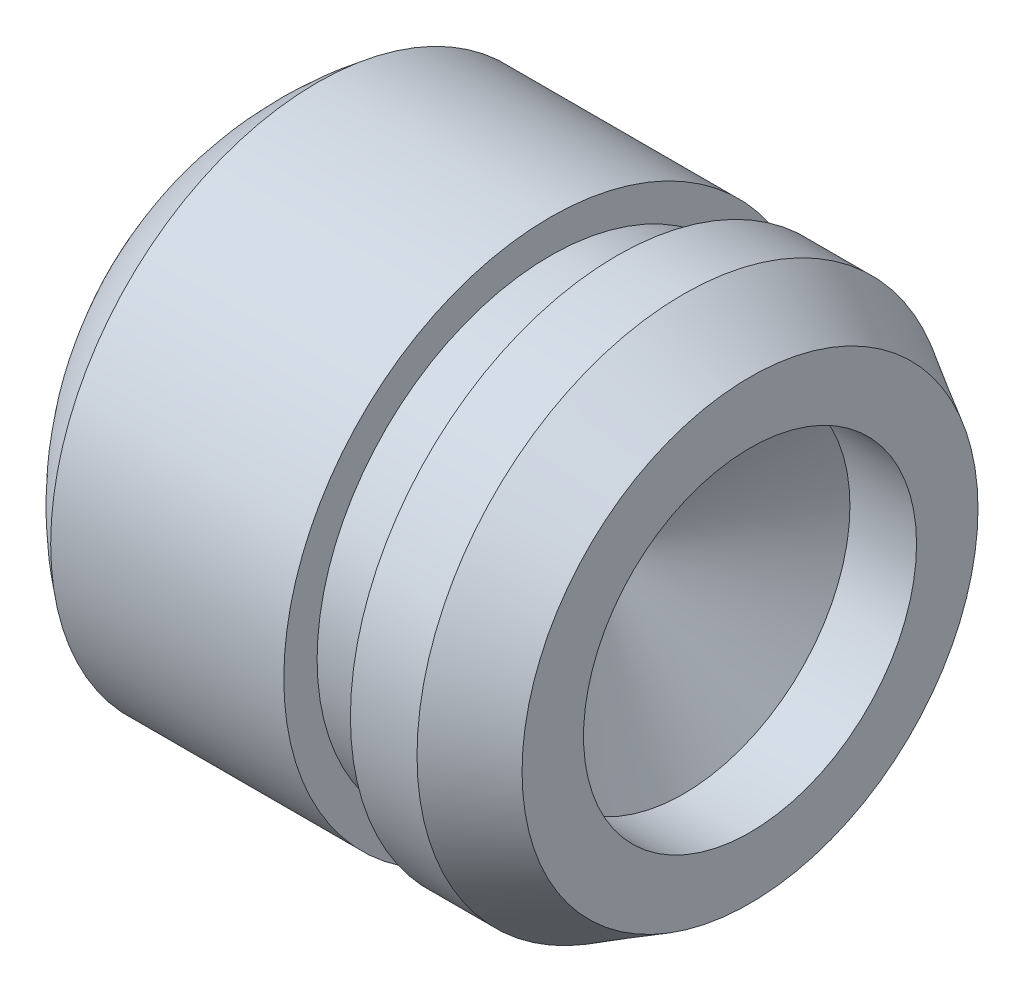
SolidWorks part; units mm, degrees
ref_plane "Front Plane" through (0, 0, 0) normal (0, 0, 1) x (1, 0, 0)
ref_plane "Top Plane" through (0, 0, 0) normal (0, 1, 0) x (1, 0, 0)
ref_plane "Right Plane" through (0, 0, 0) normal (1, 0, 0) x (0, 0, -1)
sketch "Sketch1" plane through (0, 0, 0) normal (0, 0, 1) x (1, 0, 0)
  line L0 (0, 0) -> (28.0396, 0) construction
  line L1 (17, 0) -> (17, 6.8453)
  line L2 (17, 6.8453) -> (15, 8)
  line L3 (15, 8) -> (13, 8)
  line L4 (13, 8) -> (13, 7)
  line L5 (13, 7) -> (11, 7)
  line L6 (11, 7) -> (11, 8)
  line L7 (11, 8) -> (4, 8)
  line L8 (0, 0) -> (17, 0)
  arc A0 (0, 0) -> (4, 8) centre (10, 0) cw
  point P14 (12, 7)
  dimension "D8" = 10
  dimension "D1" = 16
  dimension "D2" = 17
  dimension "D3" = 2
  dimension "D4" = 5
  dimension "D5" = 14
  dimension "D6" = 2
  dimension "D7" = 30
revolve "Revolve1" add sketch "Sketch1" angle 360 about L0
hole_wizard "Ø10.0 (10) Diameter Hole1" positions "Sketch2" profile "Sketch3" hole size "Ø10.0" standard "ISO"
sketch "Sketch2" plane through (17, 0, 0) normal (1, 0, 0) x (0, 0, -1)
  point P0 (0, 0)
sketch "Sketch3" plane through (17, 0, 0) normal (0, 1, 0) x (0, 0, -1)
  line L0 (0, 0) -> (0, 5.0043)
  line L1 (0, 5.0043) -> (5, 2)
  line L2 (5, 2) -> (5, 0)
  line L5 (5, 0) -> (0, 0)
  line L10 (0, 5.0043) -> (-5, 2) construction
  line L11 (0, -6.35) -> (0, 107.95) construction
  dimension "Hole Dia." = 10
  dimension "Hole Depth" = 2
  dimension "Drill Angle" = 118
